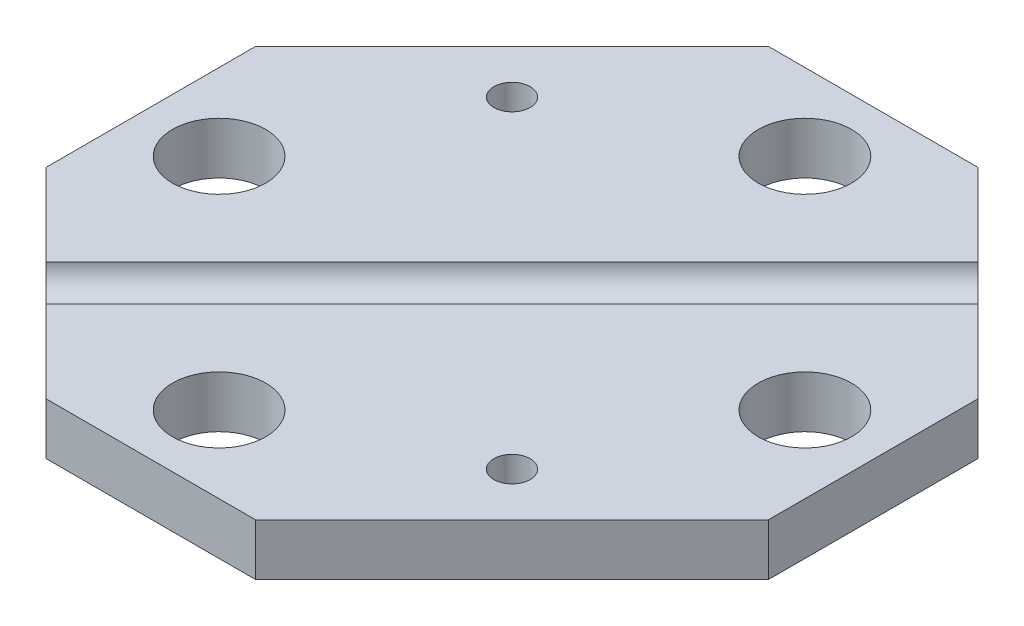
SolidWorks part; units mm, degrees
ref_plane "Front Plane" through (0, 0, 0) normal (0, 0, 1) x (1, 0, 0)
ref_plane "Top Plane" through (0, 0, 0) normal (0, 1, 0) x (1, 0, 0)
ref_plane "Right Plane" through (0, 0, 0) normal (1, 0, 0) x (0, 0, -1)
sketch "Sketch1" plane through (0, 0, 0) normal (0, 1, 0) x (1, 0, 0)
  line L0 (-40.3039, 15.5552) -> (-15.5552, 40.3039)
  line L1 (-40.3039, -40.3039) -> (40.3039, -40.3039) construction
  line L2 (-40.3039, -40.3039) -> (-40.3039, 40.3039) construction
  line L3 (-40.3039, 40.3039) -> (40.3039, 40.3039) construction
  line L4 (40.3039, -40.3039) -> (40.3039, 40.3039) construction
  line L5 (-40.3039, -40.3039) -> (40.3039, 40.3039) construction
  line L6 (-40.3039, 40.3039) -> (40.3039, -40.3039) construction
  line L7 (-27.9296, 27.9296) -> (2.476, -2.476) construction
  line L8 (-11.6661, -16.6182) -> (16.6182, 11.6661) construction
  line L9 (-11.6661, -16.6182) -> (-32.8793, 4.5951) construction
  line L10 (16.6182, 11.6661) -> (-4.5951, 32.8793) construction
  line L11 (-40.3039, 15.5552) -> (-40.3039, -4.6948)
  line L12 (-15.5552, 40.3039) -> (4.6948, 40.3039)
  line L13 (24.0428, 0.706) -> (24.0428, 20.956)
  line L14 (-0.706, -24.0428) -> (-20.956, -24.0428)
  line L15 (-32.8793, 4.5951) -> (-4.5951, 32.8793) construction
  line L16 (-18.7372, 18.7372) -> (11.6684, -11.6684) construction
  line L17 (-0.706, -24.0428) -> (24.0428, 0.706)
  line L18 (-40.3039, -4.6948) -> (-20.956, -24.0428)
  line L19 (4.6948, 40.3039) -> (24.0428, 20.956)
  circle A0 centre (-11.6661, -16.6182) radius 4.5
  circle A1 centre (16.6182, 11.6661) radius 4.5
  circle A2 centre (-4.5951, 32.8793) radius 4.5
  circle A3 centre (-32.8793, 4.5951) radius 4.5
  point P0 (0, 0)
  point P13 (2.476, -2.476)
  point P28 (11.6684, -11.6684)
  dimension "D6" = 9
  dimension "D1" = 135
  dimension "D2" = 35
  dimension "D3" = 43
  dimension "D4" = 40
  dimension "D5" = 30
  dimension "D7" = 20.25
  dimension "D8" = 20.25
  dimension "D9" = 43
  dimension "D10" = 35
  dimension "D11" = 20.25
  dimension "D12" = 20.25
extrude "Boss-Extrude1" add sketch "Sketch1" along normal blind 5
sketch "Sketch2" plane through (0, 5, 0) normal (0, 1, 0) x (1, 0, 0)
  line L0 (-27.9296, 27.9296) -> (11.6684, -11.6684) construction
  line L1 (-15.5552, 40.3039) -> (-40.3039, 15.5552) construction
  line L2 (-0.706, -24.0428) -> (24.0428, 0.706) construction
  line L3 (-18.7372, -2.476) -> (2.476, 18.7372) construction
  line L4 (-12.55, 33.7632) -> (17.502, 3.7112) construction
  line L5 (-12.55, 33.7632) -> (-33.7632, 12.55) construction
  line L6 (-33.7632, 12.55) -> (-3.7112, -17.502) construction
  line L7 (-3.7112, -17.502) -> (17.502, 3.7112) construction
  line L8 (15.7343, 5.4789) -> (13.9665, 3.7112) construction
  line L9 (13.9665, 3.7112) -> (15.7343, 1.9434) construction
  line L10 (-5.4789, -15.7343) -> (-3.7112, -13.9665) construction
  line L11 (-3.7112, -13.9665) -> (-1.9434, -15.7343) construction
  line L12 (-23.1566, 23.1566) -> (-21.3181, 21.3181) construction
  circle A0 centre (13.9665, 3.7112) radius 1.75
  circle A1 centre (-3.7112, -13.9665) radius 1.75
  circle A3 centre (-21.3181, 21.3181) radius 1.75
  point P9 (-8.1306, 8.1306)
  point P12 (2.476, 18.7372)
  dimension "D7" = 3.5
  dimension "D10" = 3.5
  dimension "D11" = 2.6
  dimension "D12" = 3.5
  dimension "D1" = 30
  dimension "D2" = 42.5
  dimension "D3" = 30
  dimension "D4" = 42.5
  dimension "D5" = 2.5
  dimension "D6" = 2.5
  dimension "D8" = 2.5
  dimension "D9" = 2.5
sketch "Sketch3" plane through (0, 5, 0) normal (0, 1, 0) x (1, 0, 0)
  line L0 (-30.63, -14.3688) -> (14.3688, 30.63) construction
  line L1 (-40.3039, -4.6948) -> (-20.956, -24.0428) construction
  line L2 (24.0428, 20.956) -> (4.6948, 40.3039) construction
sketch "Sketch4" plane through (22.4994, 0, -22.4994) normal (0.7071, 0, -0.7071) x (-0.7071, 0, -0.7071)
  line L0 (13.9984, 5) -> (8.9984, 5)
  line L1 (-2.1827, 5) -> (25.1795, 5) construction
  arc A0 (8.9984, 5) -> (13.9984, 5) centre (11.4984, 5) ccw
  point P5 (11.4984, 5)
  dimension "D1" = 5
extrude "Cut-Extrude1" cut sketch "Sketch4" against normal up to next
sketch "Sketch6" plane through (0, 5, 0) normal (0, 1, 0) x (1, 0, 0)
  line L0 (-9.8984, 9.8984) -> (-27.9296, 27.9296) construction
  line L1 (-32.3977, -12.601) -> (12.601, 32.3977) construction
  line L2 (-15.5552, 40.3039) -> (-40.3039, 15.5552) construction
  line L3 (-6.3628, 6.3628) -> (11.6684, -11.6684) construction
  line L4 (-28.8622, -16.1366) -> (16.1366, 28.8622) construction
  line L5 (-0.706, -24.0428) -> (24.0428, 0.706) construction
  circle A0 centre (-23.6869, 23.6869) radius 1.75
  circle A1 centre (7.4258, -7.4258) radius 1.75
  point P16 (0, 0)
  point P17 (0, 0)
  point P18 (0, 0)
  point P19 (0, 0)
  dimension "D1" = 3.5
  dimension "D2" = 6
  dimension "D3" = 6
extrude "Cut-Extrude3" cut sketch "Sketch6" against normal up to next
